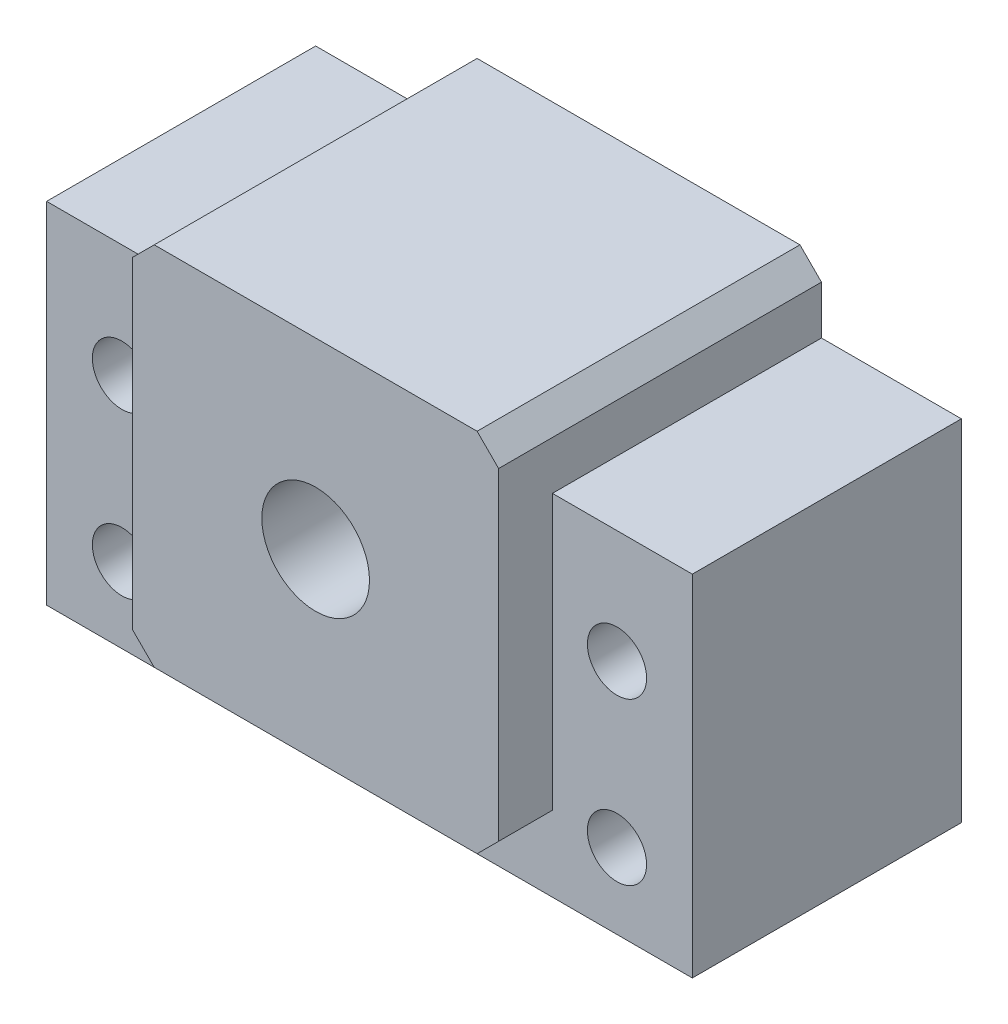
SolidWorks part; units mm, degrees
ref_plane "Front Plane" through (0, 0, 0) normal (0, 0, 1) x (1, 0, 0)
ref_plane "Top Plane" through (0, 0, 0) normal (0, 1, 0) x (1, 0, 0)
ref_plane "Right Plane" through (0, 0, 0) normal (1, 0, 0) x (0, 0, -1)
sketch "Sketch1" plane through (0, 0, 0) normal (0, 0, 1) x (1, 0, 0)
  line L0 (0, 0) -> (-17, 0) construction
  line L5 (0, 0) -> (0, 17) construction
  line L6 (15, 17) -> (-15, 17)
  line L7 (-15, 17) -> (-17, 15)
  line L8 (-17, 15) -> (-17, -15)
  line L9 (0, 0) -> (-17, 17) construction
  line L10 (-15, 17) -> (-17, 17) construction
  line L11 (-17, 15) -> (-17, 17) construction
  line L12 (17, 15) -> (17, 17) construction
  line L13 (15, 17) -> (17, 17) construction
  line L14 (0, 0) -> (17, 17) construction
  line L15 (17, 15) -> (17, -15)
  line L16 (15, 17) -> (17, 15)
  line L17 (15, -17) -> (17, -15)
  line L18 (-15, -17) -> (-17, -15)
  line L19 (15, -17) -> (-15, -17)
  circle A0 centre (0, 0) radius 5
  point P3 (-16, 16)
  point P9 (0, 0)
  point P10 (0, 0)
  point P11 (0, 0)
  point P19 (17, 0)
  dimension "D1" = 10
  dimension "D2" = 34
  dimension "D3" = 2
extrude "Boss-Extrude1" add sketch "Sketch1" along normal blind 5
sketch "Sketch2" plane through (0, 0, 0) normal (0, 0, -1) x (-1, 0, 0)
  line L0 (15, 17) -> (-15, 17)
  line L1 (-15, 17) -> (-17, 15)
  line L2 (-17, 15) -> (-17, 10.5)
  line L3 (-17, -15) -> (-17, 15) construction
  line L4 (-17, 10.5) -> (-30, 10.5)
  line L5 (-30, 10.5) -> (-30, -22)
  line L6 (-30, -22) -> (30, -22)
  line L7 (0, 17) -> (0, -22) construction
  line L8 (-23, 0) -> (-23, -15) construction
  line L9 (23, -15) -> (-23, -15) construction
  line L10 (0, 0) -> (-23, 0) construction
  line L11 (30, 10.5) -> (30, -22)
  line L12 (17, 10.5) -> (30, 10.5)
  line L13 (17, 15) -> (17, 10.5)
  line L14 (15, 17) -> (17, 15)
  circle A0 centre (0, 0) radius 5 construction
  circle A1 centre (0, 0) radius 5
  circle A2 centre (-23, 0) radius 2.75
  circle A3 centre (-23, -15) radius 2.75
  circle A4 centre (23, -15) radius 2.75
  circle A5 centre (23, 0) radius 2.75
  point P24 (0, -15)
  dimension "D3" = 5.5
  dimension "D1" = 32.5
  dimension "D2" = 39
  dimension "D4" = 60
  dimension "D5" = 46
  dimension "D6" = 15
extrude "Boss-Extrude2" add sketch "Sketch2" along normal blind 25
